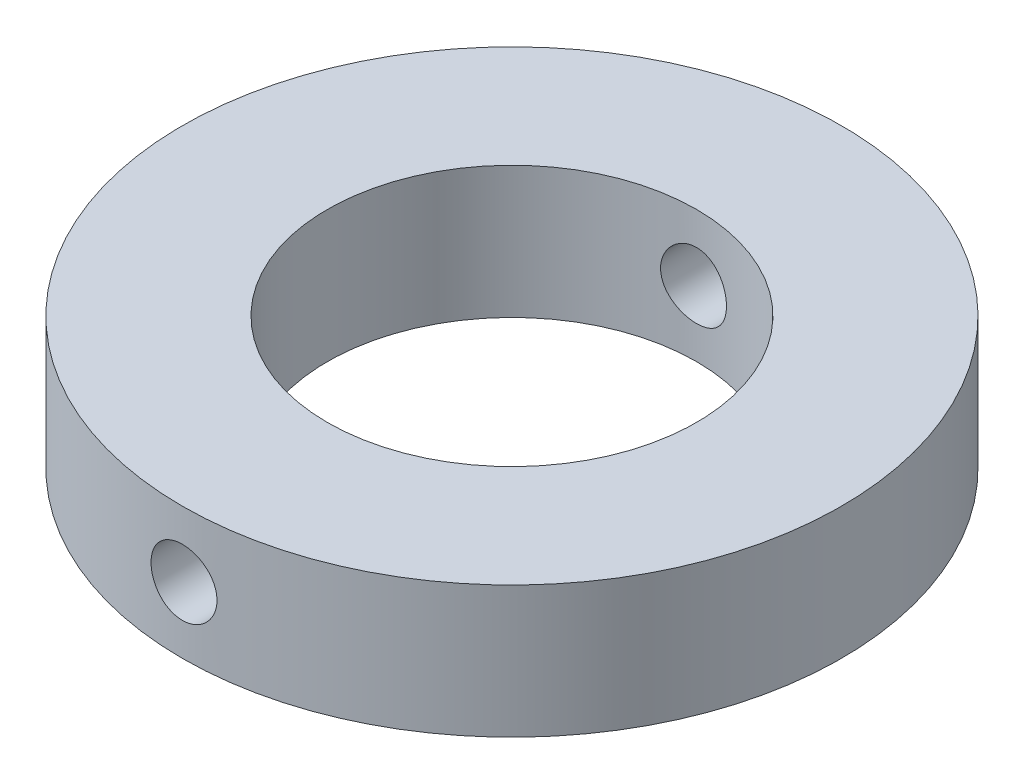
SolidWorks part; units mm, degrees
ref_plane "Front Plane" through (0, 0, 0) normal (0, 0, 1) x (1, 0, 0)
ref_plane "Top Plane" through (0, 0, 0) normal (0, 1, 0) x (1, 0, 0)
ref_plane "Right Plane" through (0, 0, 0) normal (1, 0, 0) x (0, 0, -1)
sketch "Sketch1" plane through (0, 0, 0) normal (0, 1, 0) x (1, 0, 0)
  circle A0 centre (0, 0) radius 25
  circle A1 centre (0, 0) radius 14
  dimension "D1" = 50
  dimension "D2" = 28
extrude "Boss-Extrude1" add sketch "Sketch1" along normal mid plane 10
sketch "Sketch2" plane through (0, 0, 0) normal (0, 0, 1) x (1, 0, 0)
  circle A0 centre (0, 0) radius 2.5
  dimension "D1" = 5
extrude "Cut-Extrude1" cut sketch "Sketch2" against normal mid plane 70
